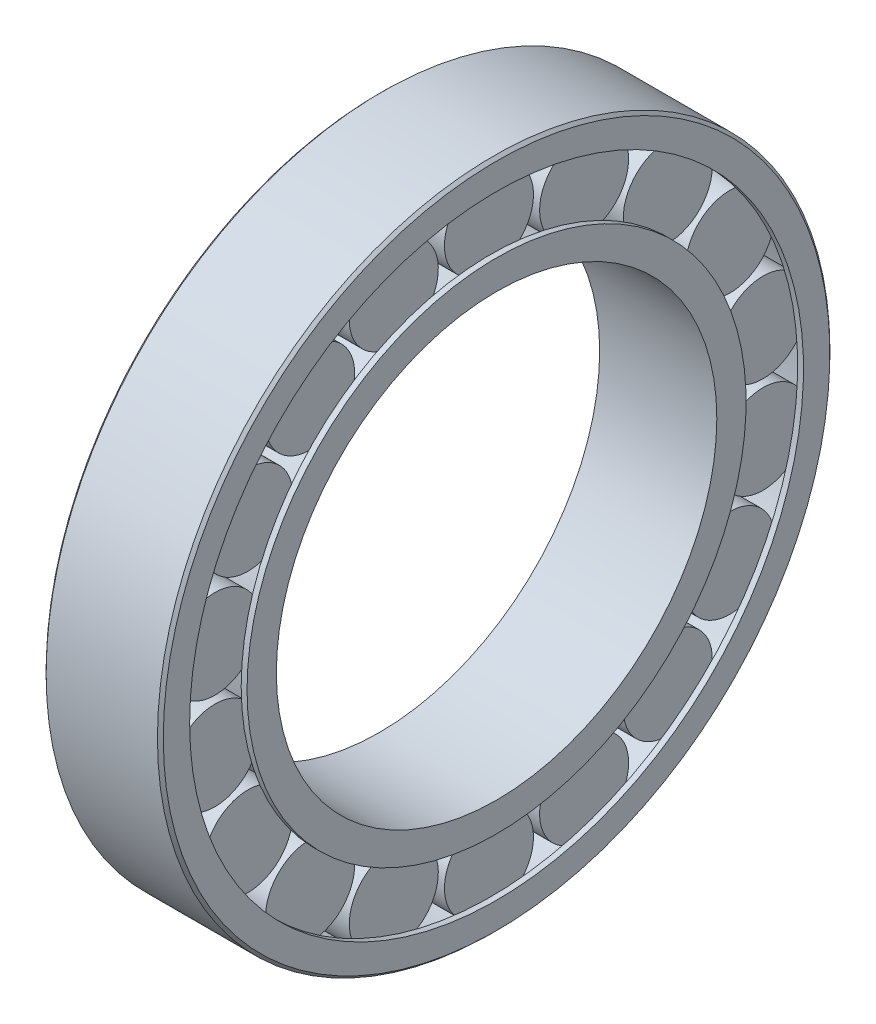
SolidWorks part; units mm, degrees
ref_plane "前视基准面" through (0, 0, 0) normal (0, 0, 1) x (1, 0, 0)
ref_plane "上视基准面" through (0, 0, 0) normal (0, 1, 0) x (1, 0, 0)
ref_plane "右视基准面" through (0, 0, 0) normal (1, 0, 0) x (0, 0, -1)
other "Configuration Table"
sketch "草图1" plane through (0, 0, 0) normal (0, 0, 1) x (1, 0, 0)
  line L0 (0, 0) -> (118.1583, 0) construction
  line L1 (0, 0) -> (0, 111.2107) construction
  line L2 (-10, 57.4) -> (10, 57.4)
  line L3 (-10, 37.6) -> (10, 37.6)
  line L4 (-10, 37.6) -> (-10, 42.6)
  line L5 (-10, 42.6) -> (-9, 42.6)
  line L6 (-9, 42.6) -> (-9, 39.6)
  line L7 (-9, 39.6) -> (9, 39.6)
  line L8 (9, 39.6) -> (9, 42.6)
  line L9 (9, 42.6) -> (10, 42.6)
  line L10 (10, 42.6) -> (10, 37.6)
  line L11 (-10, 57.4) -> (-10, 52.4)
  line L12 (-10, 52.4) -> (-9, 52.4)
  line L13 (-9, 52.4) -> (-9, 55.4)
  line L14 (-9, 55.4) -> (9, 55.4)
  line L15 (9, 52.4) -> (9, 55.4)
  line L16 (10, 52.4) -> (9, 52.4)
  line L17 (10, 57.4) -> (10, 52.4)
  point P8 (0, 37.6)
  point P9 (0, 57.4)
  point P21 (0, 55.4)
  dimension "D1" = 20
  dimension "D2" = 114.8
  dimension "D3" = 75.2
  dimension "D4" = 2
  dimension "D5" = 3
  dimension "D6" = 1
revolve "旋转1" add sketch "草图1" angle 360 about L0
sketch "草图2" plane through (0, 0, 0) normal (0, 0, 1) x (1, 0, 0)
  line L0 (9, 55.4) -> (9, -55.4) construction
  line L1 (-8.7, 55.1) -> (8.7, 55.1)
  line L2 (-8.7, 55.1) -> (-8.7, 47.5)
  line L3 (-8.7, 39.9) -> (8.7, 39.9) construction
  line L4 (8.7, 55.1) -> (8.7, 47.5)
  line L5 (-8.7, 55.1) -> (8.7, 39.9) construction
  line L6 (-8.7, 39.9) -> (8.7, 55.1) construction
  line L7 (-9, -55.4) -> (-9, 55.4) construction
  line L8 (9, 55.4) -> (-9, 55.4) construction
  line L9 (9, 39.6) -> (-9, 39.6) construction
  line L10 (-8.7, 47.5) -> (8.7, 47.5)
  line L11 (-8.7, 47.5) -> (-8.7, 39.9) construction
  line L12 (8.7, 47.5) -> (8.7, 39.9) construction
  point P0 (0, 47.5)
  dimension "D1" = 0.3
  dimension "D2" = 0.3
  dimension "D3" = 0.3
  dimension "D4" = 0.3
revolve "旋转2" add sketch "草图2" angle 360 about L10
pattern_circular "阵列(圆周)2" count 18 over 360 about axis through (0, 0, 0) along (1, 0, 0) of bodies 108
chamfer "倒角1" distance 0.5 angle 45 2 edges at (10, 0, 57.4) (-10, 0, 57.4)
